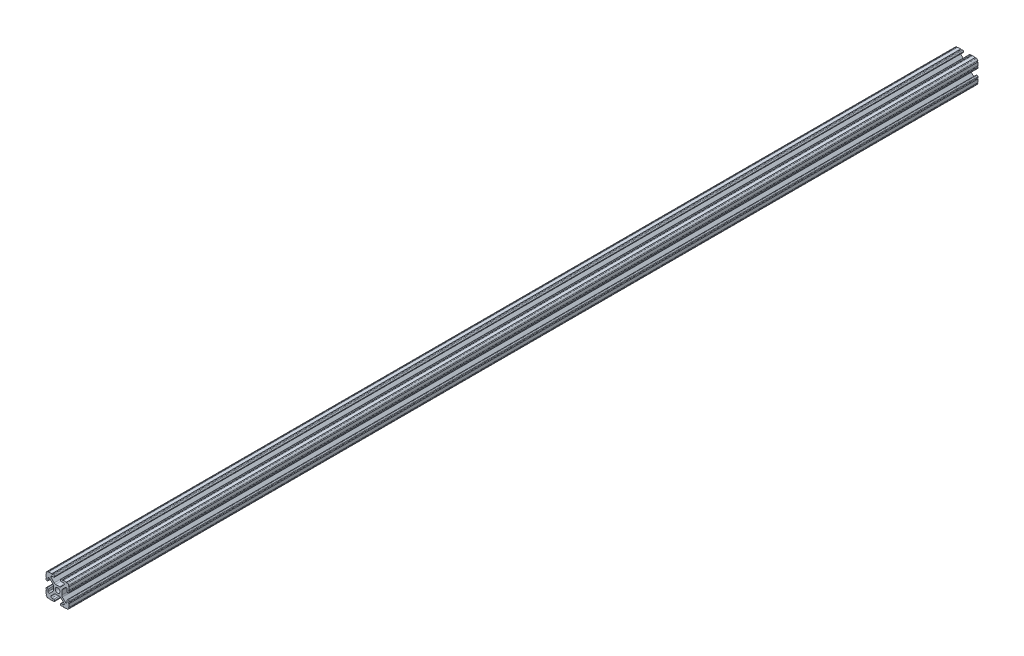
SolidWorks part; units mm, degrees
material "6061 Alloy"
ref_plane "Front Plane" through (0, 0, 0) normal (0, 0, 1) x (1, 0, 0)
ref_plane "Top Plane" through (0, 0, 0) normal (0, 1, 0) x (1, 0, 0)
ref_plane "Right Plane" through (0, 0, 0) normal (1, 0, 0) x (0, 0, -1)
sketch "Sketch2" plane through (0, 0, 0) normal (0, 0, 1) x (1, 0, 0)
  line L0 (0, 12.7) -> (0, -12.7) construction
  line L1 (-12.7, 0) -> (12.7, 0) construction
  line L2 (3.2512, -12.7) -> (12.7, -12.7)
  line L3 (12.7, -12.7) -> (12.7, -3.2512)
  line L4 (3.2512, -12.7) -> (3.2512, -10.4902)
  line L5 (3.2512, -10.4902) -> (8.9276, -10.4902)
  line L6 (8.9276, -10.4902) -> (3.0856, -4.6482)
  line L7 (0, 0) -> (12.7, -12.7) construction
  line L8 (12.7, -3.2512) -> (10.4902, -3.2512)
  line L9 (10.4902, -3.2512) -> (10.4902, -8.9276)
  line L10 (10.4902, -8.9276) -> (4.6482, -3.0856)
  circle A0 centre (0, 0) radius 2.6035
  arc A1 (6.3485, -10.4902) -> (7.1039, -8.6665) centre (6.3485, -9.4219) ccw construction
  point P8 (0, -4.6482)
  dimension "Center Hole Diameter" = 5.207
  dimension "Rail Height" = 25.4
  dimension "Rail Width" = 25.4
  dimension "T-Slot Width" = 6.5024
  dimension "Slot Inner Width" = 14.8336
  dimension "Thickness" = 2.2098
  dimension "Slot Depth" = 5.842
  dimension "D1" = 2.2098
sketch "Sketch3" plane through (0, 0, 0) normal (1, 0, 0) x (0, 0, -1)
  line L0 (-500, -12.7) -> (500, -12.7) construction
  line L1 (-474.6, 0) -> (474.6, 0) construction
  dimension "Length" = 1000
  dimension "D1" = 25.4
sketch "Sketch4" plane through (0, 0, 0) normal (0, 0, 1) x (1, 0, 0)
  line L0 (4.1904, -12.7) -> (10.1173, -12.7)
  line L1 (3.2512, -12.7) -> (12.7, -12.7) construction
  line L2 (3.2512, -12.7) -> (3.2512, -10.4902) construction
  line L3 (3.2512, -10.4902) -> (8.9276, -10.4902) construction
  line L4 (3.2512, -11.4294) -> (3.2512, -11.7608)
  line L5 (4.1904, -10.4902) -> (6.3485, -10.4902)
  line L6 (0, -4.6482) -> (2.164, -4.6482)
  line L7 (8.9276, -10.4902) -> (3.0856, -4.6482) construction
  line L8 (3.7373, -5.2999) -> (7.1039, -8.6665)
  line L9 (12.7, -12.7) -> (12.7, -3.2512) construction
  line L10 (10.4902, -8.9276) -> (4.6482, -3.0856) construction
  line L11 (10.4902, -3.2512) -> (10.4902, -8.9276) construction
  line L12 (10.4902, -6.3485) -> (10.4902, -4.1904)
  line L13 (12.7, -3.2512) -> (10.4902, -3.2512) construction
  line L14 (11.4294, -3.2512) -> (11.7608, -3.2512)
  line L15 (12.7, -4.1904) -> (12.7, -10.1173)
  line L16 (8.6665, -7.1039) -> (5.2999, -3.7373)
  line L17 (4.6482, 0) -> (4.6482, -2.164)
  line L18 (-12.7, 0) -> (12.7, 0) construction
  line L19 (0, -4.6482) -> (0, -2.6035)
  line L20 (0, 12.7) -> (0, -12.7) construction
  line L21 (4.6482, 0) -> (2.6035, 0)
  arc A0 (3.2512, -11.7608) -> (4.1904, -12.7) centre (4.1904, -11.7608) ccw
  arc A2 (3.2512, -11.4294) -> (4.1904, -10.4902) centre (4.1904, -11.4294) cw
  arc A3 (6.3485, -10.4902) -> (7.1039, -8.6665) centre (6.3485, -9.4219) ccw
  arc A4 (2.164, -4.6482) -> (3.7373, -5.2999) centre (2.164, -6.8732) cw
  arc A5 (10.1173, -12.7) -> (12.7, -10.1173) centre (10.1173, -10.1173) ccw
  arc A6 (8.6665, -7.1039) -> (10.4902, -6.3485) centre (9.4219, -6.3485) ccw
  arc A7 (10.4902, -4.1904) -> (11.4294, -3.2512) centre (11.4294, -4.1904) cw
  arc A8 (11.7608, -3.2512) -> (12.7, -4.1904) centre (11.7608, -4.1904) cw
  arc A9 (5.2999, -3.7373) -> (4.6482, -2.164) centre (6.8732, -2.164) cw
  circle A10 centre (0, 0) radius 2.6035 construction
  arc A11 (0, -2.6035) -> (2.6035, 0) centre (0, 0) ccw
  dimension "D1" = 2.5827
  dimension "D2" = 2.225
  dimension "D3" = 0.9392
extrude "Boss-Extrude1" add sketch "Sketch4" along normal mid plane 1000
sketch "Sketch5" plane through (0, 0, 0) normal (0, 0, 1) x (1, 0, 0)
  line L0 (3.2512, -12.7) -> (12.7, -12.7) construction
  line L1 (4.1904, -10.4902) -> (6.3485, -10.4902) construction
  line L3 (0, 0) -> (12.7, -12.7) construction
  line L4 (6.3485, -10.4902) -> (6.3485, -12.7) construction
  line L5 (8.9276, -10.4902) -> (3.0856, -4.6482) construction
  circle A0 centre (10.3562, -12.7) radius 0.5524
  circle A1 centre (5.796, -12.7) radius 0.5524
  circle A2 centre (12.7, -10.3562) radius 0.5524
  circle A3 centre (12.7, -5.796) radius 0.5524
  point P10 (5.2694, -10.4902)
  point P12 (9.4219, -6.3485)
  dimension "D1" = 1.1049
extrude "Cut-Extrude1" cut sketch "Sketch5" against normal through all both and the other way through all
mirror "Mirror1" about plane through (0, 0, 0) normal (1, 0, 0) of bodies 137 134
mirror "Mirror2" about plane through (0, 0, 0) normal (0, 1, 0) of bodies 135
equation "\"D1@Boss-Extrude1\"=\"Length@Sketch3\""
equation "\"D1@Sketch2\"=\"Thickness@Sketch2\""
equation "\"D2@Sketch4\"=\"Slot Inner Width@Sketch2\"*0.15"
equation "\"D1@Sketch4\"=\"D3@Sketch4\"*2.75"
equation "\"D3@Sketch4\"=\"Thickness@Sketch2\"*0.425"
equation "\"D1@Sketch5\"=\"Thickness@Sketch2\"*0.5"
